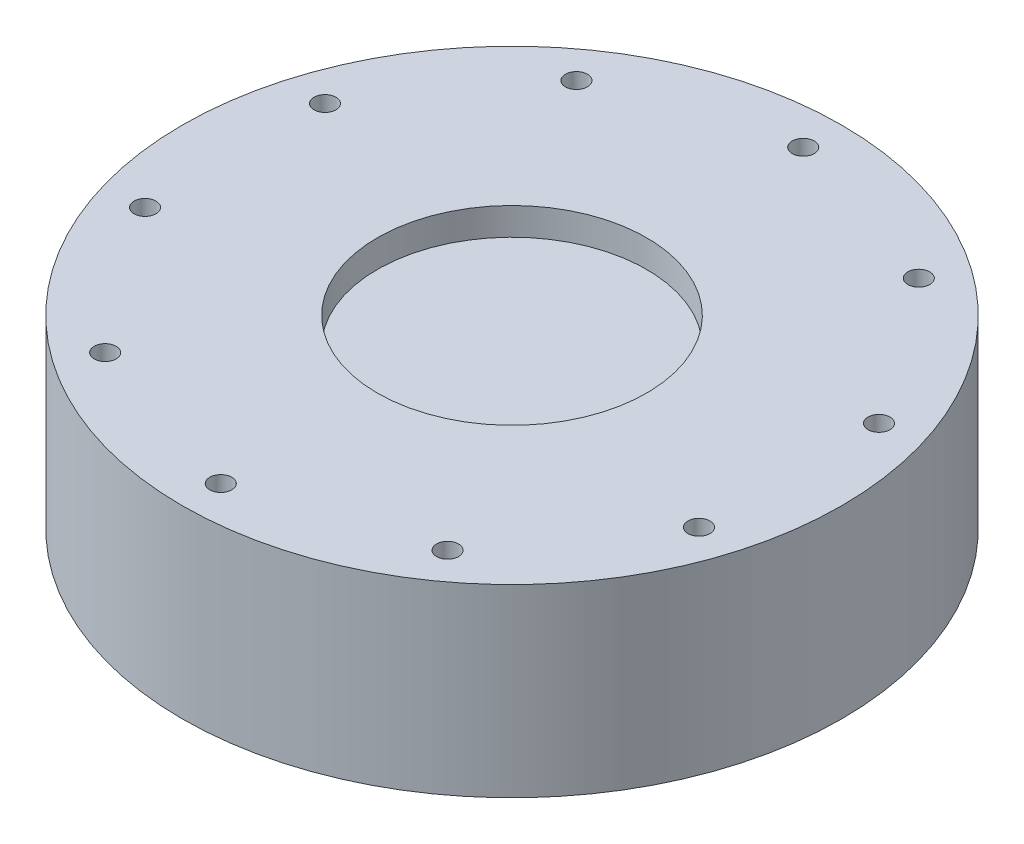
SolidWorks part; units mm, degrees
ref_plane "Front Plane" through (0, 0, 0) normal (0, 0, 1) x (1, 0, 0)
ref_plane "Top Plane" through (0, 0, 0) normal (0, 1, 0) x (1, 0, 0)
ref_plane "Right Plane" through (0, 0, 0) normal (1, 0, 0) x (0, 0, -1)
sketch "Sketch1" plane through (0, 0, 0) normal (0, 1, 0) x (1, 0, 0)
  circle A0 centre (0, 0) radius 60
extrude "Boss-Extrude1" add sketch "Sketch1" along normal blind 33.6 contours A0
sketch "Sketch2" plane through (0, 33.6, 0) normal (0, 1, 0) x (1, 0, 0)
  circle A1 centre (0, 0) radius 53 construction
  circle A2 centre (0, 53) radius 2
  circle A3 centre (31.1526, 42.8779) radius 2
  circle A4 centre (50.406, 16.3779) radius 2
  circle A5 centre (50.406, -16.3779) radius 2
  circle A6 centre (31.1526, -42.8779) radius 2
  circle A7 centre (0, -53) radius 2
  circle A8 centre (-31.1526, -42.8779) radius 2
  circle A9 centre (-50.406, -16.3779) radius 2
  circle A10 centre (-50.406, 16.3779) radius 2
  circle A11 centre (-31.1526, 42.8779) radius 2
  point P27 (0, 0)
  dimension "D1" = 10
extrude "Cut-Extrude2" cut sketch "Sketch2" against normal through all both and the other way through all
sketch "Sketch4" plane through (0, 33.6, 0) normal (0, 1, 0) x (1, 0, 0)
  circle A0 centre (0, 0) radius 24.5
extrude "Cut-Extrude3" cut sketch "Sketch4" against normal blind 5
sketch "Sketch5" plane through (0, 0, 0) normal (0, -1, 0) x (1, 0, 0)
  circle A0 centre (0, 0) radius 42.5
extrude "Boss-Extrude2" add sketch "Sketch5" along normal blind 11.5
sketch "Sketch6" plane through (0, -11.5, 0) normal (0, -1, 0) x (1, 0, 0)
  line L0 (-14.2, -40.0576) -> (14.2, -40.0576)
  line L1 (-14.2, -40.0576) -> (-14.2, -47.3068)
  line L2 (-14.2, -47.3068) -> (14.2, -47.3068)
  line L3 (14.2, -47.3068) -> (14.2, -41.015)
  circle A0 centre (0, 0) radius 42.5 construction
  dimension "D1" = 28.4
extrude "Cut-Extrude4" cut sketch "Sketch6" against normal blind 11.5 and the other way through all
